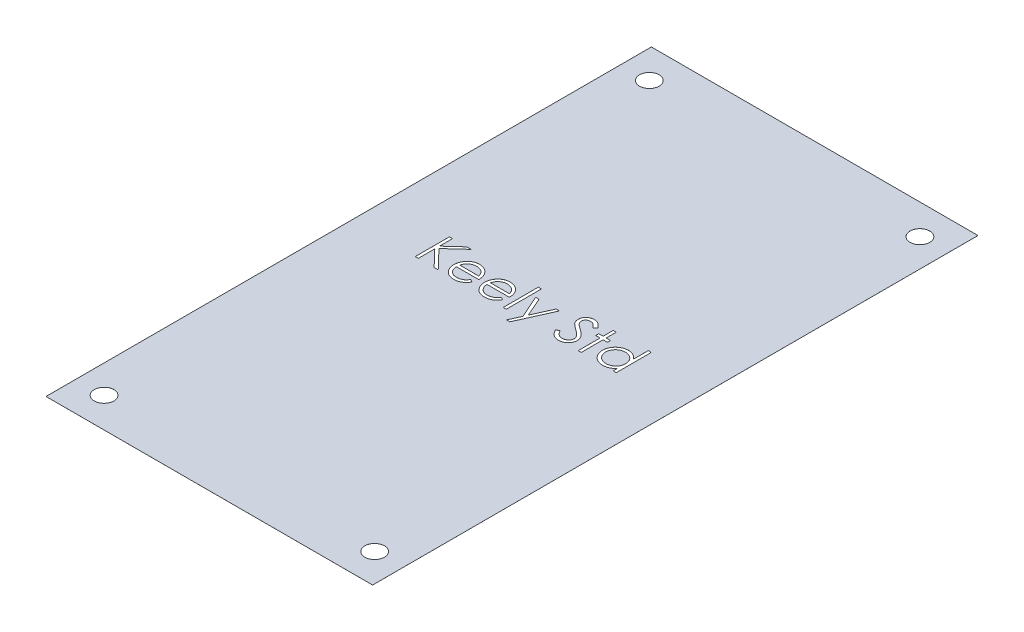
SolidWorks part; units mm, degrees
ref_plane "Front Plane" through (0, 0, 0) normal (0, 0, 1) x (1, 0, 0)
ref_plane "Top Plane" through (0, 0, 0) normal (0, 1, 0) x (1, 0, 0)
ref_plane "Right Plane" through (0, 0, 0) normal (1, 0, 0) x (0, 0, -1)
sketch "Sketch2" plane through (0, 0, 0) normal (0, 1, 0) x (1, 0, 0)
  line L1 (-30.353, -56.261) -> (30.353, -56.261)
  line L2 (-30.353, -56.261) -> (-30.353, 56.261)
  line L3 (-30.353, 56.261) -> (30.353, 56.261)
  line L4 (30.353, -56.261) -> (30.353, 56.261)
  line L5 (-30.353, -56.261) -> (30.353, 56.261) construction
  line L6 (-30.353, 56.261) -> (30.353, -56.261) construction
  point P0 (0, 0)
  dimension "D1" = 112.522
  dimension "D2" = 60.706
extrude "Boss-Extrude1" add sketch "Sketch2" along normal blind 0.0025
sketch "Sketch3" plane through (0, 0.0025, 0) normal (0, 1, 0) x (1, 0, 0)
  line L1 (-25.146, -50.673) -> (25.146, -50.673)
  line L2 (-25.146, -50.673) -> (-25.146, 50.673)
  line L3 (-25.146, 50.673) -> (25.146, 50.673)
  line L4 (25.146, -50.673) -> (25.146, 50.673)
  line L5 (-25.146, -50.673) -> (25.146, 50.673) construction
  line L6 (-25.146, 50.673) -> (25.146, -50.673) construction
  circle A0 centre (-25.146, 50.673) radius 1.8288
  circle A7 centre (25.146, 50.673) radius 1.8288
  circle A8 centre (25.146, -50.673) radius 1.8288
  circle A9 centre (-25.146, -50.673) radius 1.8288
  point P0 (0, 0)
  dimension "D3" = 3.6576
  dimension "D1" = 101.346
  dimension "D2" = 50.292
  dimension "D4" = 2
  dimension "D5" = 2
extrude "Cut-Extrude1" cut sketch "Sketch3" against normal through all contours A9 | A8 | A7 | A0
sketch "Sketch5" plane through (0, 0.0025, 0) normal (0, 1, 0) x (1, 0, 0)
  text T0 "Keely Std\r\n\r\n" font "Century Gothic" height 6.35
  point P1 (-23.0976, -2.5229)
extrude "Cut-Extrude2" cut sketch "Sketch5" against normal blind 2.54
